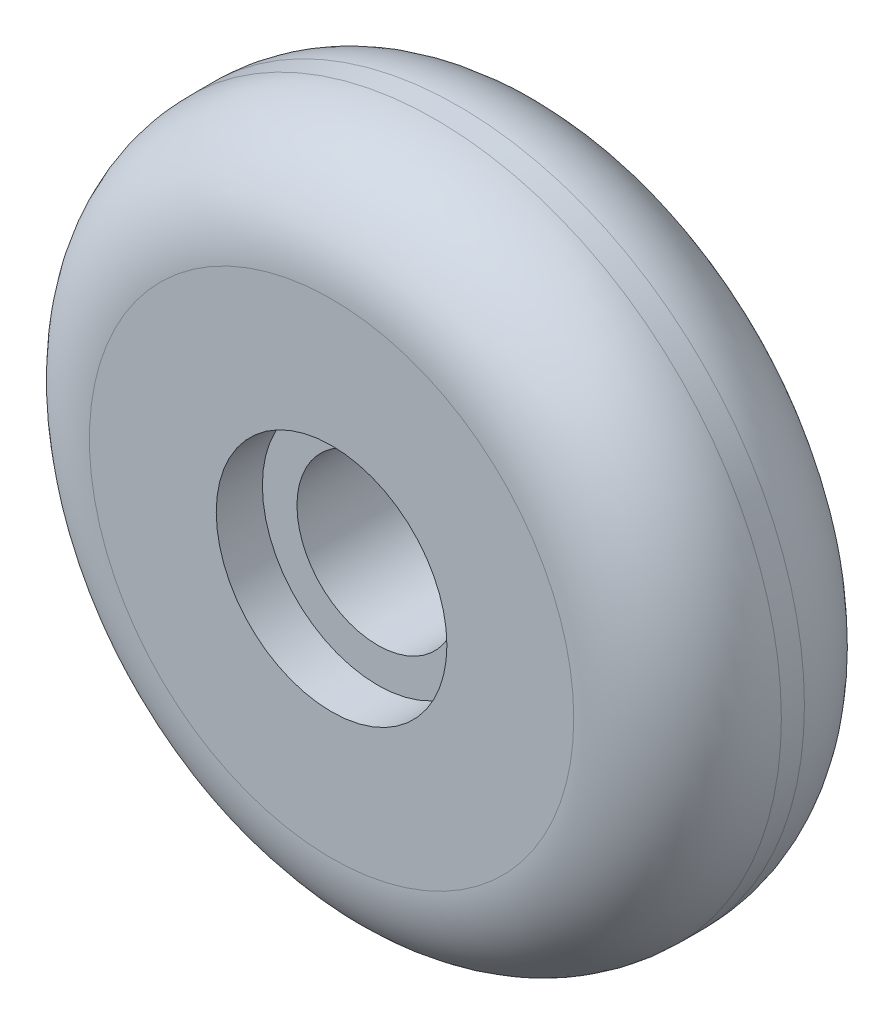
SolidWorks part; units mm, degrees
ref_plane "Front Plane" through (0, 0, 0) normal (0, 0, 1) x (1, 0, 0)
ref_plane "Top Plane" through (0, 0, 0) normal (0, 1, 0) x (1, 0, 0)
ref_plane "Right Plane" through (0, 0, 0) normal (1, 0, 0) x (0, 0, -1)
sketch "Sketch1" plane through (0, 0, 0) normal (0, 0, 1) x (1, 0, 0)
  circle A0 centre (0, 0) radius 3.5
  circle A1 centre (0, 0) radius 15
  dimension "D1" = 7
  dimension "D2" = 30
extrude "Boss-Extrude1" add sketch "Sketch1" along normal blind 10
fillet "Fillet1" radius 4.5 2 edges at (15, 0, 0) (15, 0, 10)
sketch "Sketch2" plane through (0, 0, 0) normal (0, 0, -1) x (-1, 0, 0)
  circle A0 centre (0, 0) radius 5
sketch "Sketch3" plane through (0, 0, 0) normal (0, 0, 1) x (1, 0, 0)
  circle A0 centre (0, 0) radius 5
sketch "Sketch5" plane through (0, 0, 10) normal (0, 0, 1) x (1, 0, 0)
  circle A0 centre (0, 0) radius 5
extrude "Cut-Extrude1" cut sketch "Sketch2" against normal blind 2
extrude "Cut-Extrude2" cut sketch "Sketch5" against normal blind 2
